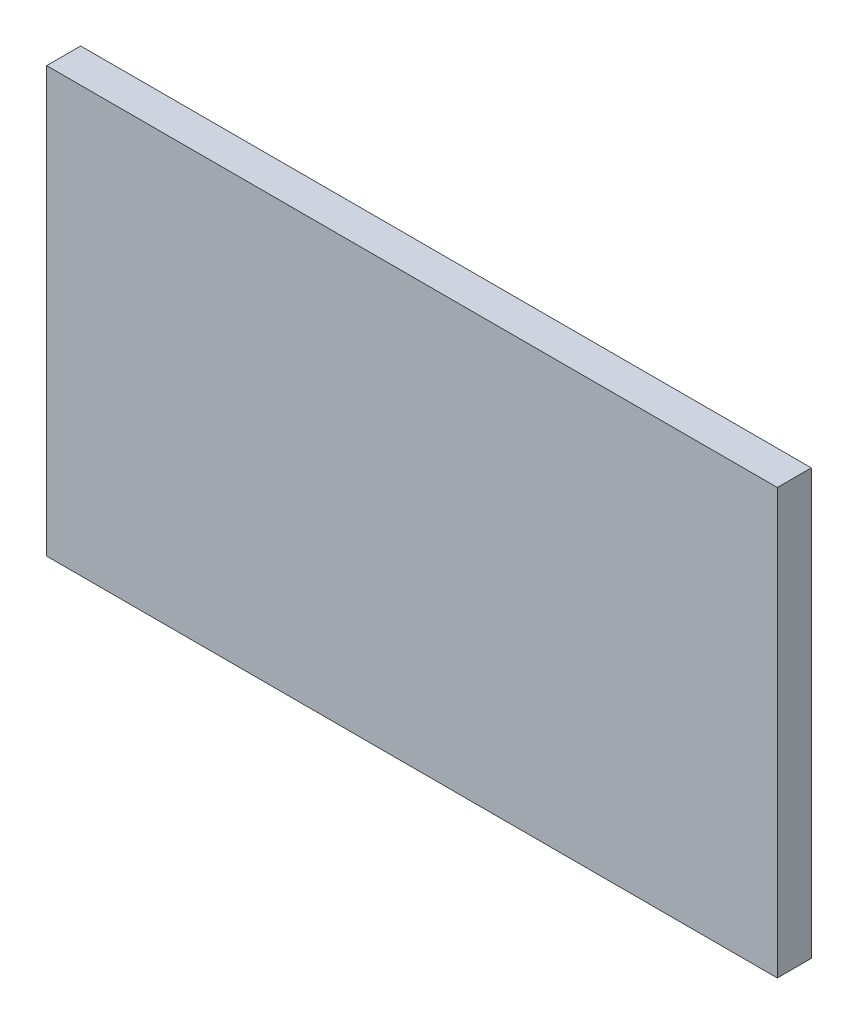
SolidWorks part; units mm, degrees
ref_plane "Płaszczyzna przednia" through (0, 0, 0) normal (0, 0, 1) x (1, 0, 0)
ref_plane "Płaszczyzna górna" through (0, 0, 0) normal (0, 1, 0) x (1, 0, 0)
ref_plane "Płaszczyzna prawa" through (0, 0, 0) normal (1, 0, 0) x (0, 0, -1)
sketch "Sketch1" plane through (0, 0, 0) normal (0, 0, 1) x (1, 0, 0)
  line L1 (0, 0) -> (86, 0)
  line L2 (0, 0) -> (0, 50)
  line L3 (0, 50) -> (86, 50)
  line L4 (86, 0) -> (86, 50)
  line L5 (0, 0) -> (86, 50) construction
  line L6 (0, 50) -> (86, 0) construction
  point P4 (43, 25)
  dimension "D1" = 86
  dimension "D2" = 50
extrude "Boss-Extrude1" add sketch "Sketch1" along normal blind 4
